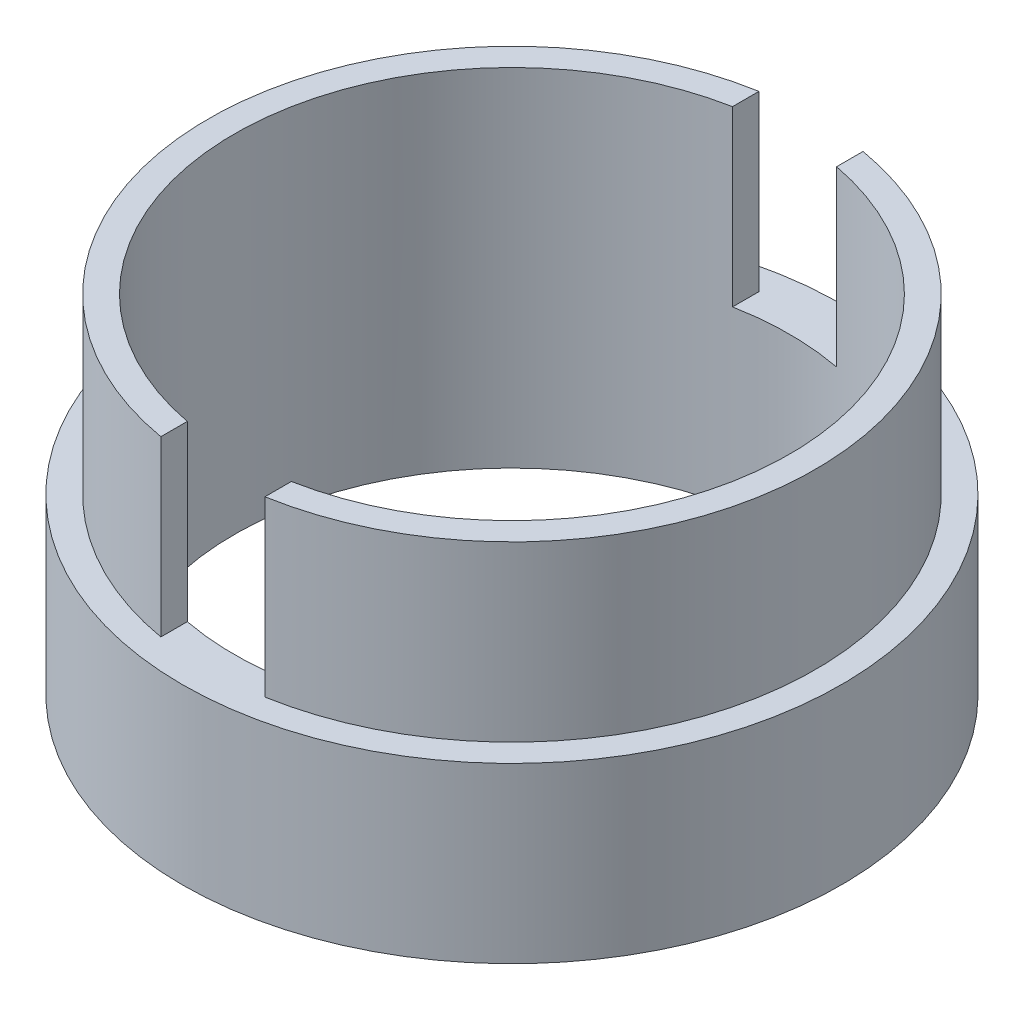
SolidWorks part; units mm, degrees
ref_plane "Front Plane" through (0, 0, 0) normal (0, 0, 1) x (1, 0, 0)
ref_plane "Top Plane" through (0, 0, 0) normal (0, 1, 0) x (1, 0, 0)
ref_plane "Right Plane" through (0, 0, 0) normal (1, 0, 0) x (0, 0, -1)
sketch "Sketch1" plane through (0, 0, 0) normal (0, 1, 0) x (1, 0, 0)
  circle A0 centre (0, 0) radius 95
  circle A1 centre (0, 0) radius 80
  dimension "D1" = 190
  dimension "D2" = 15
extrude "Boss-Extrude1" add sketch "Sketch1" along normal blind 50
sketch "Sketch2" plane through (0, 50, 0) normal (0, 1, 0) x (1, 0, 0)
  circle A0 centre (0, 0) radius 87.5
  circle A3 centre (0, 0) radius 80
  dimension "D1" = 175
  dimension "D2" = 160
extrude "Boss-Extrude2" add sketch "Sketch2" along normal blind 50
sketch "Sketch4" plane through (0, 0, 0) normal (0, 0, 1) x (1, 0, 0)
  line L0 (0, 0) -> (0, 122.7579) construction
  line L1 (-80, 0) -> (80, 0) construction
  line L2 (-86.2166, 50) -> (95, 50) construction
  line L3 (95, 50) -> (-95, 50) construction
  line L4 (0, 100) -> (-15, 100)
  line L5 (80, 100) -> (-80, 100) construction
  line L6 (-15, 100) -> (-15, 50)
  line L7 (-15, 50) -> (15, 50)
  line L8 (0, 100) -> (15, 100)
  line L9 (15, 100) -> (15, 50)
  point P15 (0, 50)
  dimension "D1" = 50
  dimension "D2" = 50
  dimension "D3" = 30
extrude "Cut-Extrude1" cut sketch "Sketch4" against normal through all both and the other way through all
scale "Scale1" scale about centroid uniform scaling yes scale factor 0.1
